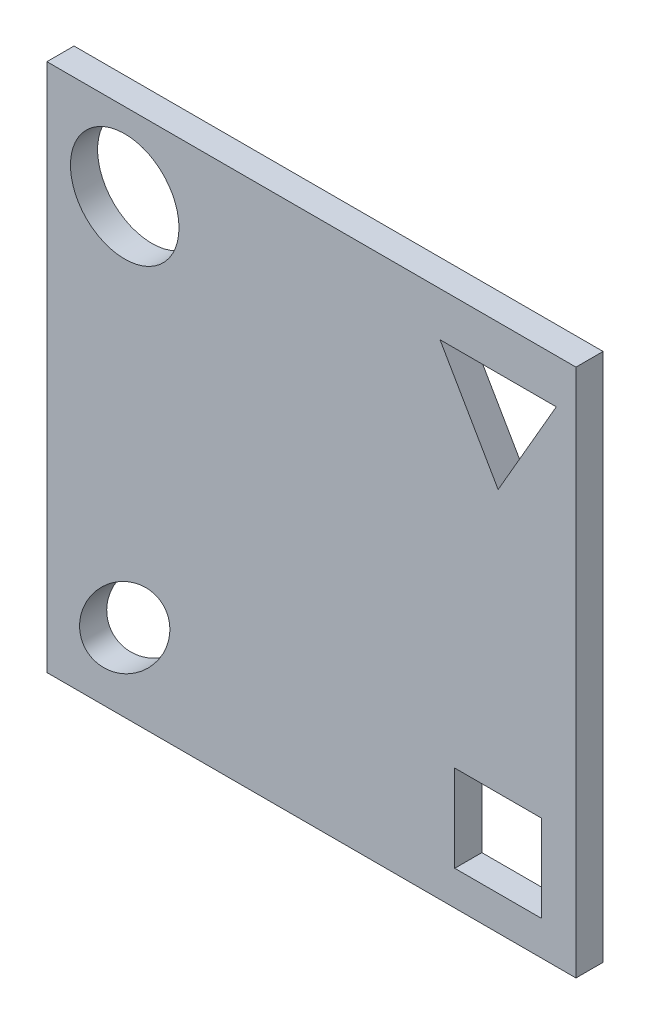
SolidWorks part; units mm, degrees
ref_plane "Front Plane" through (0, 0, 0) normal (0, 0, 1) x (1, 0, 0)
ref_plane "Top Plane" through (0, 0, 0) normal (0, 1, 0) x (1, 0, 0)
ref_plane "Right Plane" through (0, 0, 0) normal (1, 0, 0) x (0, 0, -1)
sketch "Sketch1" plane through (0, 0, 0) normal (0, 0, 1) x (1, 0, 0)
  line L1 (97.5, 97.5) -> (-97.5, 97.5)
  line L2 (97.5, 97.5) -> (97.5, -97.5)
  line L3 (97.5, -97.5) -> (-97.5, -97.5)
  line L4 (-97.5, 97.5) -> (-97.5, -97.5)
  line L5 (97.5, 97.5) -> (-97.5, -97.5) construction
  line L6 (97.5, -97.5) -> (-97.5, 97.5) construction
  line L7 (68.8195, 44.0716) -> (90.2519, 81.1935)
  line L8 (90.2519, 81.1935) -> (47.3872, 81.1935)
  line L9 (47.3872, 81.1935) -> (68.8195, 44.0716)
  line L10 (84.8209, -84.8209) -> (84.8209, -52.8182)
  line L11 (84.8209, -52.8182) -> (52.8182, -52.8182)
  line L12 (52.8182, -52.8182) -> (52.8182, -84.8209)
  line L13 (52.8182, -84.8209) -> (84.8209, -84.8209)
  circle A0 centre (-68.8195, 68.8195) radius 20
  circle A1 centre (68.8195, 68.8195) radius 12.374 construction
  circle A2 centre (68.8195, -68.8195) radius 16.0014 construction
  ellipse E0 centre (-68.8195, -68.8195) end of major axis (-54.581, -54.581) minor radius 12.1777
  point P0 (0, 0)
  dimension "D3" = 40
  dimension "D5" = 68.8195
  dimension "D2" = 195
  dimension "D4" = 37.1219
  dimension "D6" = 68.8195
  dimension "D7" = 32.0028
  dimension "D8" = 52.8182
extrude "Boss-Extrude1" add sketch "Sketch1" along normal blind 10
